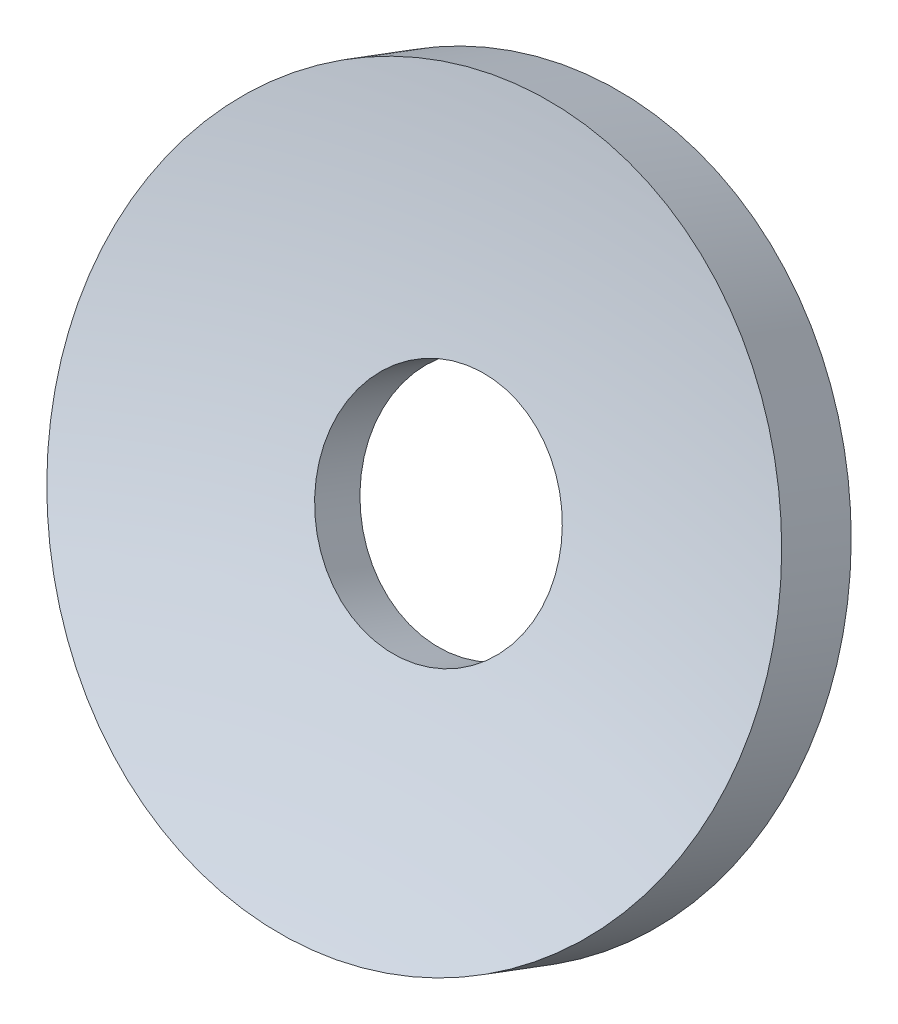
SolidWorks part; units mm, degrees
ref_plane "Plan de face" through (0, 0, 0) normal (0, 0, 1) x (1, 0, 0)
ref_plane "Plan de dessus" through (0, 0, 0) normal (0, 1, 0) x (1, 0, 0)
ref_plane "Plan de droite" through (0, 0, 0) normal (1, 0, 0) x (0, 0, -1)
ref_plane "Plan1" through (0, -1.4222, 0.591) normal (0, -0.9234, 0.3838) x (1, 0, 0)
sketch "Esquisse1" plane through (0, -1.4222, 0.591) normal (0, -0.9234, 0.3838) x (1, 0, 0)
  line L0 (49.0216, 366.325) -> (61.6785, 570.0104) construction
  line L1 (19.9191, 373.6375) -> (49.3623, 371.8079)
  line L2 (49.3623, 371.8079) -> (50.0446, 382.7867)
  line L4 (5.8974, 389.8457) -> (4.9336, 374.3358) construction
  line L5 (40.6372, 372.3501) -> (-0.7341, 374.9209) construction
  line L6 (19.9191, 373.6375) -> (20.3639, 380.7949)
  arc A2 (50.0446, 382.7867) -> (20.3639, 380.7949) centre (19.7276, 612.4141) cw
  point P4 (5.1232, 377.387)
  dimension "D4" = 231.62
  dimension "D1" = 30
  dimension "D2" = 89
  dimension "D3" = 11
revolve "Révolution1" add sketch "Esquisse1" angle 360 about L4
sketch "Esquisse2" plane through (23.2049, 143.3084, 344.8408) normal (-0.062, -0.383, -0.9217) x (-0.9981, 0.0238, 0.0573)
  circle A0 centre (18.2921, -1.5401) radius 15 construction
  circle A1 centre (18.2921, -1.5401) radius 15
  circle A2 centre (18.2921, -1.5401) radius 13
  dimension "D1" = 2
